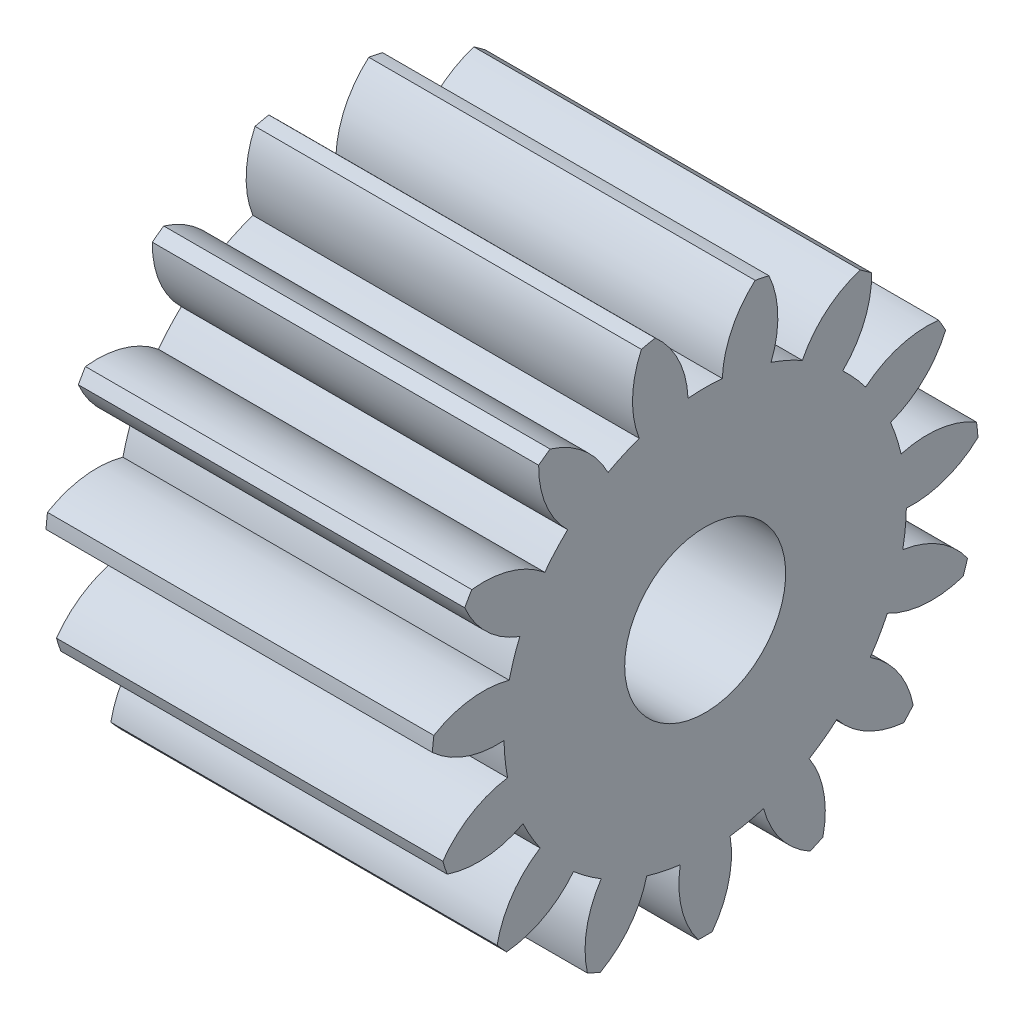
SolidWorks part; units mm, degrees
ref_plane "Plane1" through (0, 0, 0) normal (0, 0, 1) x (1, 0, 0)
ref_plane "Plane2" through (0, 0, 0) normal (0, 1, 0) x (1, 0, 0)
ref_plane "Plane3" through (0, 0, 0) normal (1, 0, 0) x (0, 0, -1)
sketch "HoldingSke" plane through (0, 0, 0) normal (0, 1, 0) x (1, 0, 0)
  line L0 (0, 0) -> (0.9659, -0.2588)
  line L1 (-15, 0) -> (100, 0) construction
  line L2 (0, 0) -> (-2.1039, 2.3779)
  line L3 (0, 0) -> (-11.863, 4.5341)
  line L4 (0, 0) -> (8.3417, 2.2352)
  line L5 (0, 0) -> (-46.8476, -17.4728)
  line L6 (0, 0) -> (-9.9476, -6.7116)
  line L7 (-2.1039, 2.3779) -> (8.6586, 51.2059)
  line L8 (-76.2, 54.61) -> (-75.3, 54.61)
  line L9 (-71.009, 38.7566) -> (-53.1078, 45.2721)
  line L10 (-76.2, 71.12) -> (104.1128, 71.12)
  line L11 (0, 0) -> (-12, 0)
  line L12 (-76.2, 101.6) -> (-76.162, 101.6)
  line L13 (24.9733, 27.94) -> (52.9518, 28.4284)
  line L14 (24.9733, 27.94) -> (24.9743, 27.94)
  line L15 (24.9733, 27.94) -> (100.4006, 29.5858)
  line L16 (-63.627, -1) -> (-12.827, -1)
  circle A0 centre (0, 0) radius 2.5
  circle A1 centre (0, 0) radius 6.249
  circle A2 centre (0, 0) radius 37.5
  circle A3 centre (0, 0) radius 2.5
  dimension "MHD" = 12.498
  dimension "Hub_dia" = 75
  dimension "Bore" = 5
  dimension "MBD" = 5
  dimension "Num_teeth" = 15
  dimension "Pitch" = 1
  dimension "Overall_len" = 50
  dimension "Show_teeth" = 15
  dimension "Thickness" = 12
  dimension "OAL" = 50.0001
  dimension "T_dim" = 0.9
  dimension "Ap" = 20
  dimension "H" = 19.05
  dimension "Pitch_radius" = 180.3128
  dimension "Width" = 12
  dimension "Backlash" = 0.038
  dimension "Addendum_fac" = 1
  dimension "Dedendum_fac" = 1.25
  dimension "Clearance_fac" = 0.25
  dimension "Dedendum_add" = 0.001
  dimension "Module" = 1
sketch "BasProSke" plane through (0, 0, 0) normal (0, 1, 0) x (1, 0, 0)
  line L0 (-10, 0) -> (60, 0) construction
  line L1 (0, 0) -> (0, 8.5)
  line L2 (0, 0) -> (12, 0)
  line L3 (12, 0) -> (12, 8.5)
  line L4 (12, 8.5) -> (0, 8.5)
  dimension "Thickness" = 12
  dimension "Diameter" = 17
revolve "Base-Revolve" add sketch "BasProSke" angle 360 about L0
sketch "TooCutSke" plane through (0, 0, 0) normal (1, 0, 0) x (0, 0, -1)
  line L1 (0, 0) -> (0, 107) construction
  line L2 (0, 0) -> (-0.8504, 7.4516) construction
  line L3 (0, 0) -> (-3.1044, 14.6049) construction
  line L4 (-0.8504, 7.4516) -> (-1.5522, 7.3025) construction
  arc A0 (0.5316, 6.2263) -> (-0.5316, 6.2263) centre (0, 0) ccw
  arc A1 (1.5766, 8.3784) -> (-1.5766, 8.3784) centre (0, 0) ccw
  circle A2 centre (0, 0) radius 7.5 construction
  circle A3 centre (0, 0) radius 7.0477 construction
  arc A4 (-0.5316, 6.2263) -> (-1.5766, 8.3784) centre (-3.5289, 6.1005) ccw
  arc A5 (1.5766, 8.3784) -> (0.5316, 6.2263) centre (3.5289, 6.1005) ccw
  dimension "Root_dia" = 12.498
  dimension "Overcut_dia" = 17.0508
  dimension "Pitch_dia" = 15
  dimension "Base_dia" = 14.0954
  dimension "Flank_rad" = 3
  dimension "Half_ang" = 12
  dimension "Half_CT" = 0.7175
extrude "ToothCut" cut sketch "TooCutSke" along normal through all
fillet "Breaks" [suppressed] radius 0.02
fillet "RootFillets" [suppressed] radius 0.251
pattern_circular "TeethCuts" count 15 every 24 about axis through (-10, 0, 0) along (1, 0, 0) of "ToothCut", "RootFillets", "Breaks"
sketch "HubNeaOneSke" plane through (0, 0, 0) normal (-1, 0, 0) x (0, 0, 1)
  circle A0 centre (0, 0) radius 6.249
  dimension "Diameter" = 12.498
extrude "HubNearOne" [suppressed] add sketch "HubNeaOneSke" along normal blind 38.0001
sketch "HubNeaBotSke" plane through (0, 0, 0) normal (-1, 0, 0) x (0, 0, 1)
  circle A0 centre (0, 0) radius 6.249
  dimension "Diameter" = 12.498
extrude "HubNearBoth" [suppressed] add sketch "HubNeaBotSke" along normal blind 19
ref_plane "FarPln" through (12, 0, 0) normal (1, 0, 0) x (0, 0, -1)
sketch "HubFarSke" plane through (12, 0, 0) normal (1, 0, 0) x (0, 0, -1)
  circle A0 centre (0, 0) radius 6.249
  dimension "Diameter" = 12.498
extrude "HubFar" [suppressed] add sketch "HubFarSke" along normal blind 19
sketch "BorSke" plane through (0, 0, 0) normal (1, 0, 0) x (0, 0, -1)
  circle A0 centre (0, 0) radius 2.5
  dimension "Diameter" = 5
extrude "Bore" cut sketch "BorSke" along normal mid plane 100.0001
sketch "KeySke" plane through (0, 0, 0) normal (1, 0, 0) x (0, 0, -1)
  line L0 (-1, 0) -> (-1, 3.4)
  line L1 (-1, 3.4) -> (1, 3.4)
  line L2 (1, 3.4) -> (1, 0)
  line L3 (0, 0) -> (0, 34) construction
  line L4 (-1, 0) -> (1, 0)
  dimension "Offset" = 3.4
  dimension "Width" = 2
extrude "Keyway" [suppressed] cut sketch "KeySke" along normal mid plane 100.0001
pattern_circular "Keyway2" [suppressed] count 2 every 90 about axis through (-10, 0, 0) along (1, 0, 0)
equation "' \"Module@HoldingSke\" = 6.35"
equation "' \"Num_teeth@HoldingSke\" = 12"
equation "' \"Ap@HoldingSke\" =  20"
equation "' \"Ap@HoldingSke\" = 20"
equation "' \"Width@HoldingSke\" = 0.5 * 25.4"
equation "' \"Hub_dia@HoldingSke\"= 1 * 25.4"
equation "' \"Hub_dia@HoldingSke\" = 1 * 25.4"
equation "' \"Overall_len@HoldingSke\" = 1.0 * 25.4"
equation "' \"Bore@HoldingSke\" = 0.75 * 25.4"
equation "' \"T_dim@HoldingSke\" = 0.1 * 25.4"
equation "' \"Width@KeySke\" = 0.25 * 25.4"
equation "' \"Show_teeth@HoldingSke\" = 13"
equation "' \"Backlash@HoldingSke\" = 0.009 * 25.4"
equation "' \"Addendum_fac@HoldingSke\" = 1.0"
equation "' \"Dedendum_fac@HoldingSke\" = 1.25"
equation "' \"Dedendum_add@HoldingSke\" = 0.00005 * 25.4"
equation "' \"Clearance_fac@HoldingSke\" = 0.25"
equation "\"Pitch@HoldingSke\" = 1 / \"Module@HoldingSke\""
equation "\"Overcut_dia@TooCutSke\" = (\"Num_teeth@HoldingSke\" + 2 * \"Addendum_fac@HoldingSke\") / \"Pitch@HoldingSke\" + 0.002 * 25.4"
equation "\"Pitch_dia@TooCutSke\" = \"Num_teeth@HoldingSke\" / \"Pitch@HoldingSke\""
equation "\"Base_dia@TooCutSke\" = \"Num_teeth@HoldingSke\" / \"Pitch@HoldingSke\" * cos((\"Ap@HoldingSke\"  * 3.14159265 / 180))"
equation "\"Root_dia@TooCutSke\" = (\"Num_teeth@HoldingSke\" + 2) / \"Pitch@HoldingSke\" - 2 * (\"Addendum_fac@HoldingSke\" + \"Dedendum_fac@HoldingSke\") / \"Pitch@HoldingSke\" - \"Dedendum_add@HoldingSke\" * 2"
equation "\"Half_ang@TooCutSke\" = 180 / \"Num_teeth@HoldingSke\""
equation "\"Half_CT@TooCutSke\" = \"Num_teeth@HoldingSke\" / \"Pitch@HoldingSke\" * sin((3.14159265 / 2 / \"Num_teeth@HoldingSke\")) / 2 - 7 * \"Backlash@HoldingSke\" / 4"
equation "\"Flank_rad@TooCutSke\" = \"Num_teeth@HoldingSke\" / \"Pitch@HoldingSke\" / 5"
equation "\"Radius@RootFillets\" = \"Clearance_fac@HoldingSke\" / \"Pitch@HoldingSke\" + \"Dedendum_add@HoldingSke\""
equation "\"Break_rad@Breaks\" = 0.02 / \"Pitch@HoldingSke\""
equation "\"Thickness@HoldingSke\" = \"Width@HoldingSke\""
equation "\"OAL@HoldingSke\" = \"Thickness@HoldingSke\""
equation "\"MHD@HoldingSke\" = (\"Num_teeth@HoldingSke\" + 2) / \"Pitch@HoldingSke\" - 2 * (\"Addendum_fac@HoldingSke\" + \"Dedendum_fac@HoldingSke\")  / \"Pitch@HoldingSke\" - \"Dedendum_add@HoldingSke\" * 2"
equation "\"MBD@HoldingSke\" = (\"Num_teeth@HoldingSke\" + 2) / \"Pitch@HoldingSke\" - 2 * (\"Addendum_fac@HoldingSke\" + \"Dedendum_fac@HoldingSke\")  / \"Pitch@HoldingSke\" - \"Dedendum_add@HoldingSke\" * 2 - 0.002 * 25.4"
equation "\"MHD@HoldingSke\" = ((sgn( \"MHD@HoldingSke\" - \"Hub_dia@HoldingSke\" )-1)*( \"MHD@HoldingSke\" - \"Hub_dia@HoldingSke\" ))/-2+ \"Hub_dia@HoldingSke\""
equation "\"MBD@HoldingSke\" = ((sgn( \"MBD@HoldingSke\" - \"Bore@HoldingSke\" )-1)*( \"MBD@HoldingSke\" - \"Bore@HoldingSke\" ))/-2+ \"Bore@HoldingSke\""
equation "\"OAL@HoldingSke\" = ((sgn( \"OAL@HoldingSke\" - \"Overall_len@HoldingSke\" )+1)*( \"OAL@HoldingSke\" - \"Overall_len@HoldingSke\" ))/2 + \"Overall_len@HoldingSke\" + 0.000002 * 25.4"
equation "\"Num_teeth@TeethCuts\" = int( \"Show_teeth@HoldingSke\" ) + 1"
equation "\"Num_teeth@TeethCuts\" = ((sgn( \"Num_teeth@TeethCuts\" - \"Num_teeth@HoldingSke\" )-1)*( \"Num_teeth@TeethCuts\" - \"Num_teeth@HoldingSke\" ))/-2+ \"Num_teeth@HoldingSke\""
equation "\"Num_teeth@TeethCuts\" = ((sgn( \"Num_teeth@TeethCuts\" - 2.0)+1)*( \"Num_teeth@TeethCuts\" - 2.0))/2 +2.0"
equation "\"Angle@TeethCuts\" = 360.0 / \"Num_teeth@HoldingSke\""
equation "\"Diameter@BasProSke\" = (\"Num_teeth@HoldingSke\" + 2 * \"Addendum_fac@HoldingSke\") / \"Pitch@HoldingSke\""
equation "\"Thickness@BasProSke\"  = \"Thickness@HoldingSke\""
equation "' \"Fillet_rad@BasProSke\" =  \"Thickness@HoldingSke\" * 0.05"
equation "' \"Fillet_rad@BasProSke\" = \"Thickness@HoldingSke\" * 0.05"
equation "\"MHD@HoldingSke\" = ((sgn( \"MHD@HoldingSke\" - \"Root_dia@TooCutSke\" )-1)*( \"MHD@HoldingSke\" - \"Root_dia@TooCutSke\" ))/-2+ \"Root_dia@TooCutSke\""
equation "\"Diameter@HubNeaOneSke\" = \"MHD@HoldingSke\""
equation "\"Length@HubNearOne\" = \"OAL@HoldingSke\" - \"Thickness@BasProSke\""
equation "\"Diameter@HubNeaBotSke\" = \"MHD@HoldingSke\""
equation "\"Length@HubNearBoth\" = ( \"OAL@HoldingSke\" - \"Thickness@BasProSke\" ) / 2.0"
equation "\"Thickness@FarPln\" = \"Thickness@BasProSke\""
equation "\"Diameter@HubFarSke\" = \"MHD@HoldingSke\""
equation "\"Length@HubFar\" = ( \"OAL@HoldingSke\" - \"Thickness@BasProSke\" ) / 2.0"
equation "\"Diameter@BorSke\" = \"MBD@HoldingSke\""
equation "\"D1@Bore\" = \"OAL@HoldingSke\" * 2.0"
equation "\"D1@Keyway\" = \"OAL@HoldingSke\" * 2.0"
equation "\"Offset@KeySke\" = \"T_dim@HoldingSke\" + \"MBD@HoldingSke\" / 2.0"
